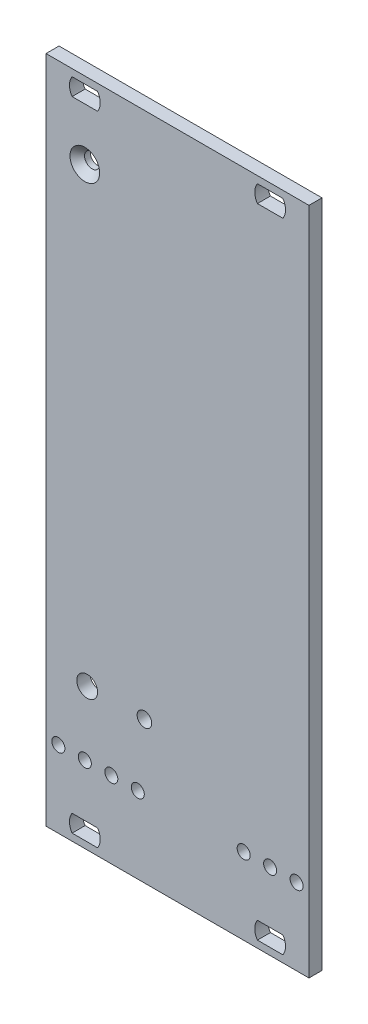
SolidWorks part; units mm, degrees
material "Alliage 1060"
ref_plane "Face" through (0, 0, 0) normal (0, 0, 1) x (1, 0, 0)
ref_plane "Dessus" through (0, 0, 0) normal (0, 1, 0) x (1, 0, 0)
ref_plane "Droite" through (0, 0, 0) normal (1, 0, 0) x (0, 0, -1)
sketch "Model" plane through (0, 0, 0) normal (0, 0, 1) x (1, 0, 0)
  line L0 (0, 128.4) -> (50.46, 128.4)
  line L1 (50.46, 0) -> (0, 0)
  line L2 (9.8954, 123.75) -> (5.0046, 123.75)
  line L3 (5.0046, 127.05) -> (9.8954, 127.05)
  line L4 (9.8954, 1.35) -> (5.0046, 1.35)
  line L5 (5.0046, 4.65) -> (9.8954, 4.65)
  line L6 (0, 0) -> (0, 128.4)
  line L7 (50.46, 128.4) -> (50.46, 0)
  line L8 (7.45, 125.4) -> (7.45, 3) construction
  line L9 (7.45, 4.65) -> (7.45, 1.35) construction
  line L10 (7.45, 127.05) -> (7.45, 123.75) construction
  line L11 (25.23, 128.4) -> (25.23, 0) construction
  line L12 (40.5646, 1.35) -> (45.4554, 1.35)
  line L13 (45.4554, 4.65) -> (40.5646, 4.65)
  line L14 (40.5646, 123.75) -> (45.4554, 123.75)
  line L15 (45.4554, 127.05) -> (40.5646, 127.05)
  circle A0 centre (2.37, 14.7) radius 1.25
  circle A1 centre (12.53, 14.7) radius 1.25
  circle A2 centre (37.93, 14.7) radius 1.25
  circle A3 centre (7.45, 14.7) radius 1.25
  arc A4 (5.0046, 4.65) -> (5.0046, 1.35) centre (7.45, 3) ccw
  circle A5 centre (7.45, 113.7) radius 1.45
  arc A6 (5.0046, 127.05) -> (5.0046, 123.75) centre (7.45, 125.4) ccw
  arc A7 (9.8954, 1.35) -> (9.8954, 4.65) centre (7.45, 3) ccw
  arc A8 (9.8954, 123.75) -> (9.8954, 127.05) centre (7.45, 125.4) ccw
  circle A9 centre (17.61, 14.7) radius 1.25
  circle A10 centre (43.01, 14.7) radius 1.25
  circle A11 centre (48.09, 14.7) radius 1.25
  arc A12 (40.5646, 1.35) -> (40.5646, 4.65) centre (43.01, 3) cw
  arc A13 (45.4554, 4.65) -> (45.4554, 1.35) centre (43.01, 3) cw
  arc A14 (45.4554, 127.05) -> (45.4554, 123.75) centre (43.01, 125.4) cw
  arc A15 (40.5646, 123.75) -> (40.5646, 127.05) centre (43.01, 125.4) cw
  point P28 (7.45, 3)
  point P31 (7.45, 125.4)
  dimension "D3" = 2.9
  dimension "D4" = 2.5
  dimension "D5" = 5.08
  dimension "D10" = 2.95
  dimension "D15" = 2.95
  dimension "D1" = 128.4
  dimension "D2" = 35.56
  dimension "D6" = 5.08
  dimension "D7" = 5.08
  dimension "D8" = 3
  dimension "D9" = 14.7
  dimension "D11" = 99
  dimension "D12" = 7.45
  dimension "D13" = 3.3
  dimension "D14" = 3
  dimension "D16" = 3.3
  dimension "D17" = 50.46
extrude "Boss.-Extru.1" add sketch "Model" along normal blind 2.5
chamfer "Chanfrein1" distance 1.4 angle 45 1 edges at (8.9, 113.7, 2.5)
sketch "Esquisse1" plane through (0, 0, 2.5) normal (0, 0, 1) x (1, 0, 0)
  circle A6 centre (18.8874, 27.2116) radius 1.4
  circle A13 centre (7.9006, 27.2005) radius 2
  dimension "D14" = 4
extrude "Enlèv. mat.-Extru.1" cut sketch "Esquisse1" against normal through all
